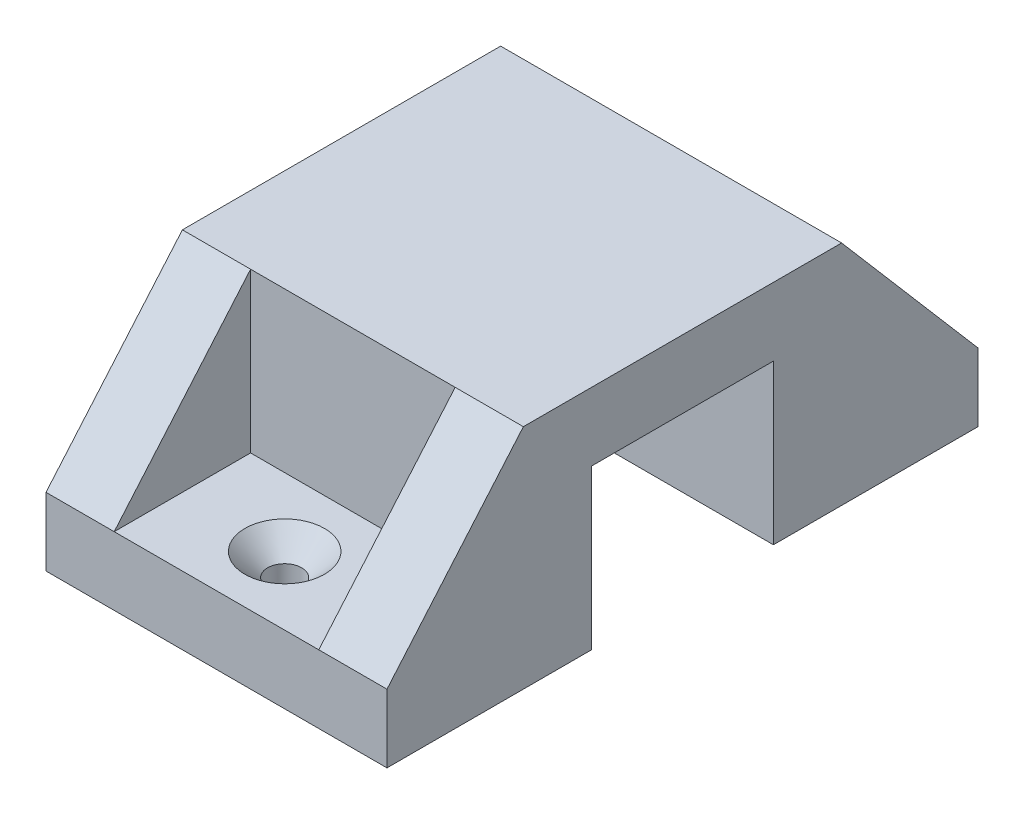
SolidWorks part; units mm, degrees
ref_plane "Front Plane" through (0, 0, 0) normal (0, 0, 1) x (1, 0, 0)
ref_plane "Top Plane" through (0, 0, 0) normal (0, 1, 0) x (1, 0, 0)
ref_plane "Right Plane" through (0, 0, 0) normal (1, 0, 0) x (0, 0, -1)
sketch "Sketch1" plane through (0, 0, 0) normal (0, 1, 0) x (1, 0, 0)
  line L1 (-15, -14) -> (15, -14)
  line L2 (-15, -14) -> (-15, 14)
  line L3 (-15, 14) -> (15, 14)
  line L4 (15, -14) -> (15, 14)
  line L5 (-15, -14) -> (15, 14) construction
  line L6 (-15, 14) -> (15, -14) construction
  point P0 (0, 0)
  dimension "D1" = 28
  dimension "D2" = 30
extrude "Boss-Extrude1" add sketch "Sketch1" along normal blind 20
sketch "Sketch2" plane through (15, 0, 0) normal (1, 0, 0) x (0, 0, -1)
  line L0 (-8, 0) -> (-8, 14)
  line L1 (-14, 0) -> (14, 0) construction
  line L2 (-8, 14) -> (8, 14)
  line L3 (8, 14) -> (8, 0)
  line L4 (8, 0) -> (-8, 0)
  line L5 (-14, 20) -> (-14, 0) construction
  dimension "D1" = 16
  dimension "D2" = 6
  dimension "D3" = 14
extrude "Cut-Extrude1" cut sketch "Sketch2" against normal through all
sketch "Sketch3" plane through (0, 0, 14) normal (0, 0, 1) x (1, 0, 0)
  line L0 (15, 20) -> (15, 0) construction
  line L1 (-15, 0) -> (15, 0)
  line L2 (-15, 0) -> (-15, 6)
  line L3 (-15, 6) -> (15, 6)
  line L4 (15, 0) -> (15, 6)
  dimension "D1" = 6
extrude "Boss-Extrude2" add sketch "Sketch3" along normal blind 12
ref_plane "Plane1" through (15, 0, 0) normal (1, 0, 0) x (0, 0, -1)
sketch "Sketch4" plane through (15, 0, 0) normal (1, 0, 0) x (0, 0, -1)
  line L0 (-14, 20) -> (-26, 6)
rib "Rib11" sketch "Sketch4" sketch "Sketch4" thickness 6 extrusion direction parallel to sketch draft on no parameters "D1"=6
mirror "Mirror1" about plane through (0, 0, 0) normal (1, 0, 0) of "Rib11"
mirror "Mirror2" about plane through (0, 0, 0) normal (0, 0, 1) of "Mirror1", "Rib11", "Boss-Extrude2"
sketch "Sketch6" plane through (0, 6, 0) normal (0, 1, 0) x (1, 0, 0)
  line L0 (9, -14) -> (-9, -14) construction
  line L1 (-9, -26) -> (-9, -14) construction
  circle A0 centre (0, -20) radius 1.5
  point P2 (0, -20.2726)
  dimension "D1" = 3
  dimension "D3" = 9
  dimension "D2" = 6
extrude "Cut-Extrude2" cut sketch "Sketch6" against normal through all
chamfer "Chamfer1" distance 2 1 edges at (0, 6, 21.5)
mirror "Mirror7" about plane through (0, 0, 0) normal (0, 0, 1) of "Cut-Extrude2"
chamfer "Chamfer2" distance 2 1 edges at (0, 6, -21.5)
